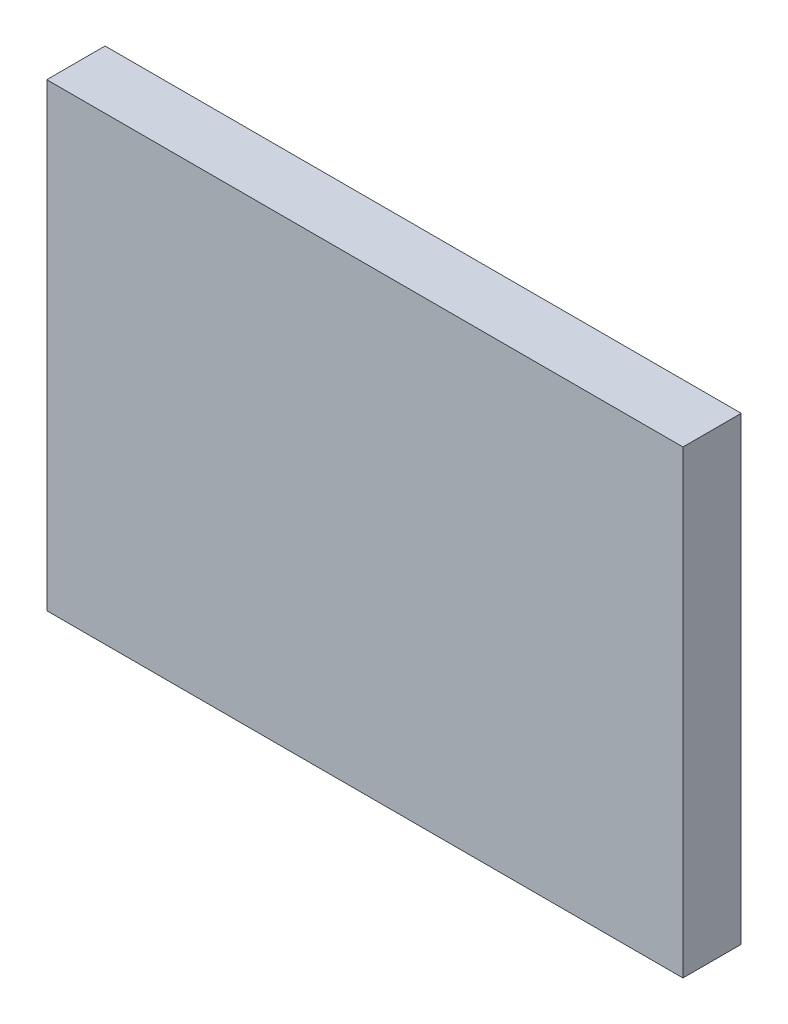
SolidWorks part; units mm, degrees
ref_plane "Ebene vorne" through (0, 0, 0) normal (0, 0, 1) x (1, 0, 0)
ref_plane "Ebene oben" through (0, 0, 0) normal (0, 1, 0) x (1, 0, 0)
ref_plane "Ebene rechts" through (0, 0, 0) normal (1, 0, 0) x (0, 0, -1)
sketch "Skizze1" plane through (0, 0, 0) normal (0, 0, 1) x (1, 0, 0)
  line L1 (6.912, 0) -> (0, 0)
  line L2 (6.912, 0) -> (6.912, 3.888)
  line L3 (6.912, 3.888) -> (0, 3.888)
  line L4 (0, 0) -> (0, 3.888)
  dimension "D1" = 6.912
  dimension "D2" = 3.888
extrude "Aufsatz-Linear austragen1" add sketch "Skizze1" along normal blind 1 contours L2 L1 L4 L3
sketch "Skizze2" plane through (0, 0, 1) normal (0, 0, 1) x (1, 0, 0)
  line L0 (6.912, 3.888) -> (0, 3.888) construction
  line L1 (-2, 5.888) -> (8.912, 5.888)
  line L2 (-2, 5.888) -> (-2, -2)
  line L3 (-2, -2) -> (8.912, -2)
  line L4 (8.912, 5.888) -> (8.912, -2)
  line L5 (6.912, 0) -> (6.912, 3.888) construction
  line L6 (6.912, 0) -> (0, 0) construction
  line L7 (0, 0) -> (0, 3.888) construction
  dimension "D1" = 2
  dimension "D2" = 2
  dimension "D3" = 2
  dimension "D4" = 2
extrude "Aufsatz-Linear austragen2" add sketch "Skizze2" along normal blind 1 contours L2 L1 L4 L3
sketch3d "3D-Skizze1"
  point P0 (3.0972, 2.5054, 0)
sketch "Skizze3" plane through (0, 0, 0) normal (0, 0, -1) x (-1, 0, 0)
  line L1 (-3.956, 2.444) -> (-2.956, 2.444)
  line L2 (-3.956, 2.444) -> (-3.956, 1.444)
  line L3 (-3.956, 1.444) -> (-2.956, 1.444)
  line L4 (-2.956, 2.444) -> (-2.956, 1.444)
  line L5 (-6.912, 0) -> (-6.912, 3.888) construction
  line L7 (0, 0) -> (0, 3.888) construction
  line L9 (-6.912, 0) -> (0, 0) construction
  line L10 (-3.456, 3.888) -> (-3.456, 0) construction
  line L11 (-6.912, 3.888) -> (0, 3.888) construction
  line L12 (-6.912, 0) -> (0, 0) construction
  line L13 (-6.912, 1.944) -> (0, 1.944) construction
  line L14 (0, 0) -> (0, 3.888) construction
  line L15 (-3.956, 2.444) -> (-2.956, 1.444) construction
  line L16 (-3.956, 1.444) -> (-2.956, 2.444) construction
  line L17 (-3.956, 1.944) -> (-3.456, 2.444)
  line L18 (-3.956, 1.944) -> (-3.4611, 1.4491)
  line L19 (-3.456, 2.444) -> (-2.9611, 1.9491)
  line L20 (-3.4611, 1.4491) -> (-2.9611, 1.9491)
  point P22 (-3.456, 1.944)
  point P23 (-3.456, 1.944)
  dimension "D1" = 1
  dimension "D2" = 1
  dimension "D3" = 0.7071
  dimension "D4" = 2.956
  dimension "D6" = 1.444
extrude "Aufsatz-Linear austragen3" add sketch "Skizze3" along normal blind 0.48 contours L17 L18 L20 L19
sketch "Skizze6" plane through (1.006, -1.006, 0) normal (0.7071, -0.7071, 0) x (0, 0, -1)
  line L0 (0, 4.1719) -> (0.48, 3.472) construction
  line L1 (0, 3.472) -> (0.48, 4.1719) construction
  line L2 (0.48, 4.1719) -> (0.24, 3.822)
  line L3 (0.24, 3.822) -> (0.48, 3.472)
  line L4 (0.48, 3.472) -> (0.48, 4.1719)
extrude "Schnitt-Linear austragen1" cut sketch "Skizze6" against normal blind 40.48
